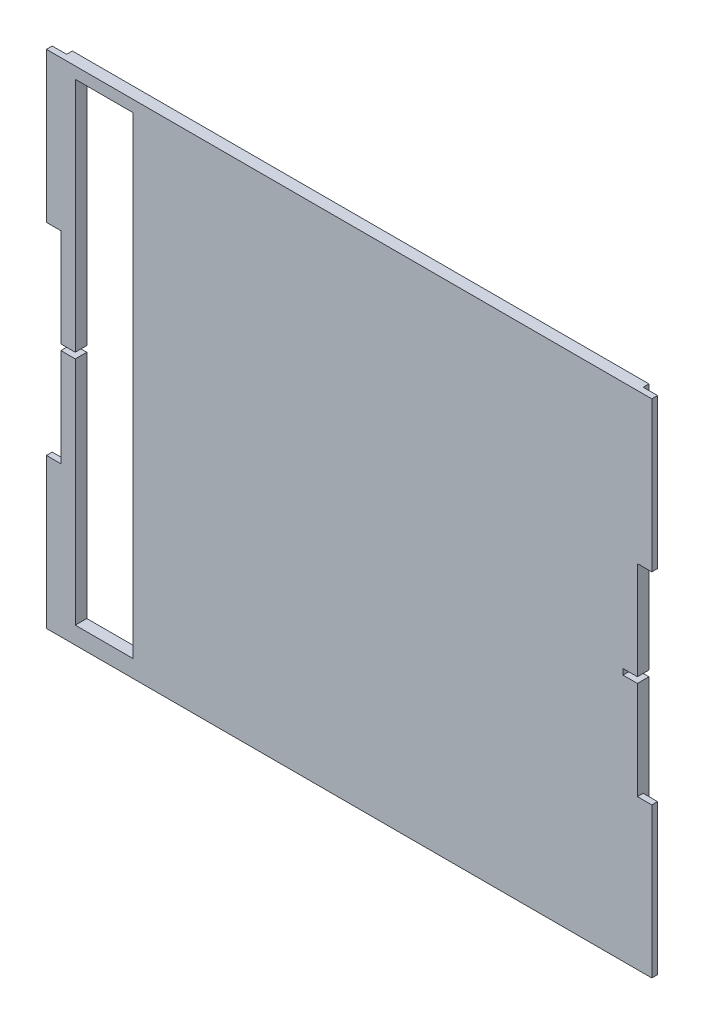
SolidWorks part; units mm, degrees
ref_plane "前视基准面" through (0, 0, 0) normal (0, 0, 1) x (1, 0, 0)
ref_plane "上视基准面" through (0, 0, 0) normal (0, 1, 0) x (1, 0, 0)
ref_plane "右视基准面" through (0, 0, 0) normal (1, 0, 0) x (0, 0, -1)
sketch "草图1" plane through (0, 0, 0) normal (0, 0, 1) x (1, 0, 0)
  line L48 (104.5, 35) -> (104.5, 87)
  line L49 (104.5, 87) -> (-105.5, 87)
  line L54 (-105.5, 35) -> (-105.5, 87)
  line L55 (-105.5, -35) -> (-105.5, -87)
  line L57 (104.5, -87) -> (-105.5, -87)
  line L58 (104.5, -35) -> (104.5, -87)
  line L63 (-105.5, 35) -> (-100.5, 35)
  line L64 (-100.5, 35) -> (-100.5, -35)
  line L65 (-100.5, -35) -> (-105.5, -35)
  line L66 (104.5, 35) -> (99.5, 35)
  line L67 (99.5, 35) -> (99.5, -35)
  line L69 (99.5, -35) -> (104.5, -35)
  line L71 (-95.5, 35) -> (-95.5, 83)
  line L72 (-95.5, 83) -> (-75.5, 83)
  line L73 (-75.5, 83) -> (-75.5, -81)
  line L74 (-75.5, -81) -> (-95.5, -81)
  line L75 (-95.5, -81) -> (-95.5, 35)
extrude "凸台-拉伸1" add sketch "草图1" along normal blind 2
sketch "草图2" plane through (0, 0, 0) normal (0, 0, 1) x (1, 0, 0)
  line L2 (104.5, 87) -> (-105.5, 87) construction
  line L3 (99.5, 87) -> (-100.5, 87)
  line L4 (-100.5, 87) -> (-100.5, -87)
  line L7 (99.5, 87) -> (99.5, -87)
  line L8 (99.5, -87) -> (-100.5, -87)
  line L10 (-95.5, 83) -> (-75.5, 83)
  line L11 (-95.5, 83) -> (-95.5, -81)
  line L12 (-95.5, -81) -> (-75.5, -81)
  line L13 (-75.5, 83) -> (-75.5, -81)
extrude "凸台-拉伸2" add sketch "草图2" against normal blind 2
sketch "草图3" plane through (0, 0, 0) normal (0, 0, 1) x (1, 0, 0)
  line L1 (-100.5, 35) -> (-100.5, -35) construction
  line L2 (-100.5, 0) -> (-100.5, 1)
  line L3 (-100.5, 1) -> (-95.5, 1)
  line L4 (-95.5, 83) -> (-95.5, -81) construction
  line L5 (-95.5, 1) -> (-95.5, -1)
  line L6 (-95.5, -1) -> (-100.5, -1)
  line L7 (-100.5, -1) -> (-100.5, 1)
  line L12 (99.5, -87) -> (99.5, 87) construction
  line L13 (99.5, 0) -> (99.5, 1)
  line L14 (99.5, 1) -> (94.5, 1)
  line L15 (94.5, 1) -> (94.5, -1)
  line L16 (94.5, -1) -> (99.5, -1)
  line L17 (99.5, -1) -> (99.5, 0)
extrude "切除-拉伸1" cut sketch "草图3" against normal through all both and the other way through all
